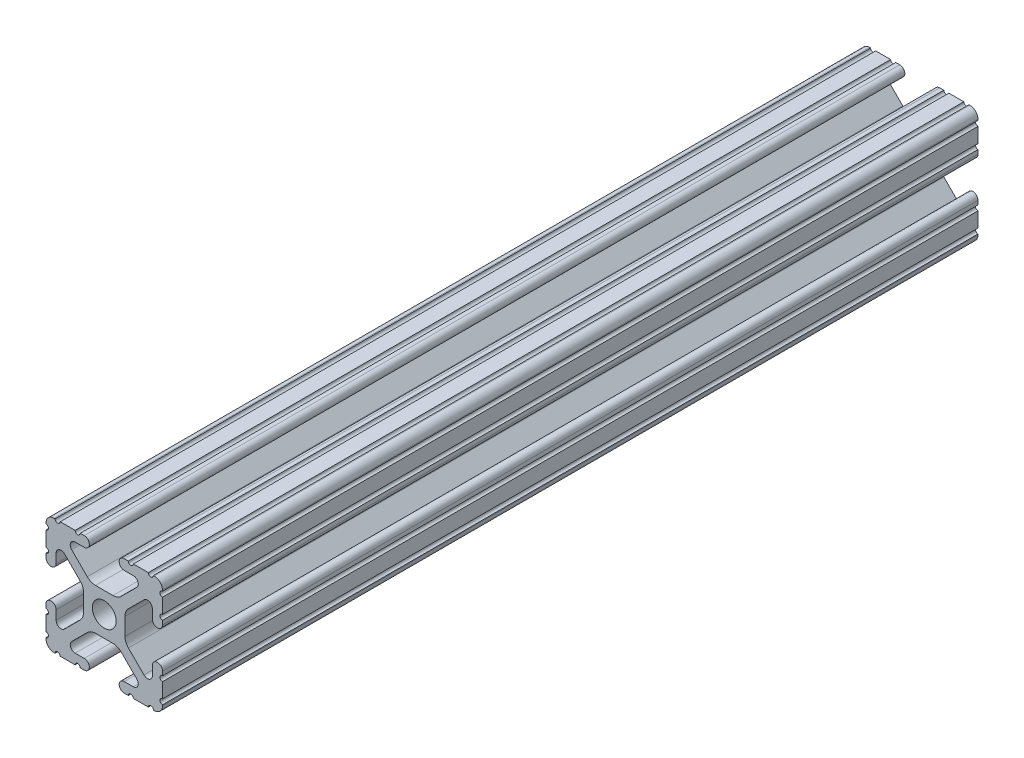
SolidWorks part; units mm, degrees
ref_plane "Front Plane" through (0, 0, 0) normal (0, 0, 1) x (1, 0, 0)
ref_plane "Top Plane" through (0, 0, 0) normal (0, 1, 0) x (1, 0, 0)
ref_plane "Right Plane" through (0, 0, 0) normal (1, 0, 0) x (0, 0, -1)
sketch "Sketch1" plane through (0, 0, 0) normal (0, 0, 1) x (1, 0, 0)
  line L0 (0, -12.7) -> (0, 12.7) construction
  line L1 (12.7, 0) -> (-12.7, 0) construction
  line L2 (3.2512, 12.7) -> (-3.2512, 12.7) construction
  line L3 (0, -4.5212) -> (0, 4.5212) construction
  line L4 (-3.2512, 12.7) -> (-3.2512, 10.4902) construction
  line L5 (12.7, -7.4168) -> (12.7, 7.4168) construction
  line L6 (0, -2.6035) -> (0, 2.6035) construction
  point P4 (0, 0)
  point P8 (0, 0)
  point P11 (0, 12.7)
  point P14 (0, 0)
  point P18 (12.7, 0)
  point P21 (0, 0)
sketch "Sketch2" plane through (0, 0, 0) normal (1, 0, 0) x (0, 0, -1)
  line L0 (-457.2, 0) -> (457.2, 0) construction
  point P4 (0, 0)
  dimension "Length" = 914.4
sketch "Sketch3" plane through (0, 0, 0) normal (0, 0, 1) x (1, 0, 0)
  line L1 (12.7, -12.7) -> (-12.7, -12.7)
  line L2 (12.7, -12.7) -> (12.7, 12.7)
  line L3 (12.7, 12.7) -> (-12.7, 12.7)
  line L4 (-12.7, -12.7) -> (-12.7, 12.7)
  line L5 (12.7, -12.7) -> (-12.7, 12.7) construction
  line L6 (12.7, 12.7) -> (-12.7, -12.7) construction
  point P0 (0, 0)
extrude "Boss-Extrude1" add sketch "Sketch3" along normal blind 177.8
sketch "Sketch4" plane through (0, 0, 177.8) normal (0, 0, 1) x (1, 0, 0)
  line L0 (-3.2512, 12.7) -> (-3.2512, 10.4902)
  line L1 (-3.2512, 10.4902) -> (-8.9276, 10.4902)
  line L2 (-8.9276, 10.4902) -> (-2.9586, 4.5212)
  line L3 (-2.9586, 4.5212) -> (2.9586, 4.5212)
  line L4 (0, -12.7) -> (0, 12.7) construction
  line L5 (12.7, 12.7) -> (-12.7, 12.7) construction
  line L6 (0, 12.7) -> (0, -12.7) construction
  line L7 (-12.7, 0) -> (12.7, 0) construction
  line L8 (-12.7, 12.7) -> (0, 0) construction
  line L9 (-12.7, 3.2512) -> (-10.4902, 3.2512)
  line L10 (-10.4902, 3.2512) -> (-10.4902, 8.9276)
  line L11 (-10.4902, 8.9276) -> (-4.5212, 2.9586)
  line L12 (-4.5212, 2.9586) -> (-4.5212, -2.9586)
  line L13 (4.5212, 2.9586) -> (4.5212, -2.9586)
  line L14 (10.4902, 8.9276) -> (4.5212, 2.9586)
  line L15 (10.4902, 3.2512) -> (10.4902, 8.9276)
  line L16 (12.7, 3.2512) -> (10.4902, 3.2512)
  line L17 (8.9276, 10.4902) -> (2.9586, 4.5212)
  line L18 (3.2512, 10.4902) -> (8.9276, 10.4902)
  line L19 (3.2512, 12.7) -> (3.2512, 10.4902)
  line L20 (3.2512, -12.7) -> (3.2512, -10.4902)
  line L21 (3.2512, -10.4902) -> (8.9276, -10.4902)
  line L22 (8.9276, -10.4902) -> (2.9586, -4.5212)
  line L23 (12.7, -3.2512) -> (10.4902, -3.2512)
  line L24 (10.4902, -3.2512) -> (10.4902, -8.9276)
  line L25 (10.4902, -8.9276) -> (4.5212, -2.9586)
  line L26 (-10.4902, -8.9276) -> (-4.5212, -2.9586)
  line L27 (-10.4902, -3.2512) -> (-10.4902, -8.9276)
  line L28 (-12.7, -3.2512) -> (-10.4902, -3.2512)
  line L29 (-2.9586, -4.5212) -> (2.9586, -4.5212)
  line L30 (-8.9276, -10.4902) -> (-2.9586, -4.5212)
  line L31 (-3.2512, -10.4902) -> (-8.9276, -10.4902)
  line L32 (-3.2512, -12.7) -> (-3.2512, -10.4902)
  line L33 (-12.7, 3.2512) -> (-12.7, -3.2512)
  line L34 (-3.2512, -12.7) -> (3.2512, -12.7)
  line L35 (12.7, -3.2512) -> (12.7, 3.2512)
  line L36 (3.2512, 12.7) -> (-3.2512, 12.7)
  line L37 (-12.7, 12.7) -> (-12.7, -12.7) construction
  line L38 (-12.7, -12.7) -> (12.7, -12.7) construction
  arc A3 (-6.3485, 10.4902) -> (-7.1039, 8.6665) centre (-6.3485, 9.4219) ccw
  arc A4 (7.1039, 8.6665) -> (6.3485, 10.4902) centre (6.3485, 9.4219) ccw
  arc A5 (8.6665, -7.1039) -> (10.4902, -6.3485) centre (9.4219, -6.3485) ccw
  arc A6 (10.4902, 6.3485) -> (8.6665, 7.1039) centre (9.4219, 6.3485) ccw
  arc A7 (-7.1039, -8.6665) -> (-6.3485, -10.4902) centre (-6.3485, -9.4219) ccw
  arc A8 (6.3485, -10.4902) -> (7.1039, -8.6665) centre (6.3485, -9.4219) ccw
  arc A9 (-8.6665, 7.1039) -> (-10.4902, 6.3485) centre (-9.4219, 6.3485) ccw
  arc A10 (-10.4902, -6.3485) -> (-8.6665, -7.1039) centre (-9.4219, -6.3485) ccw
  circle A11 centre (0, 0) radius 2.6035
  point P34 (0, 4.5212)
  point P45 (4.5212, 0)
  point P46 (-4.5212, 0)
  point P53 (0, -4.5212)
  point P81 (0, 0)
  line M2 (-12.7, 12.7) -> (-12.7, -12.7)
  line M3 (-12.7, -12.7) -> (12.7, -12.7)
  line M4 (12.7, -12.7) -> (12.7, 12.7)
  line M5 (12.7, 12.7) -> (-12.7, 12.7)
  dimension "D5" = 5.207
  dimension "D1" = 2.2098
  dimension "D2" = 2.2098
  dimension "D3" = 14.8336
  dimension "D4" = 4
extrude "Cut-Extrude1" cut sketch "Sketch4" against normal through all contours L17 A4 L18 L19 L0 L1 A3 L2 L3 M5 | L15 A6 L14 L13 L25 A5 L24 L23 L16 M4 | L21 A8 L22 L29 L30 A7 L31 L32 L20 M3 | L27 A10 L26 L12 L11 A9 L10 L9 L28 M2 | A11
sketch "Sketch5" plane through (0, 0, 177.8) normal (0, 0, 1) x (1, 0, 0)
  line L0 (-4.3561, 12.7) -> (-3.2512, 12.7)
  line L1 (-3.2512, 12.7) -> (-3.2512, 10.4902)
  line L2 (-3.2512, 10.4902) -> (-4.3561, 10.4902)
  line L3 (0, -12.7) -> (0, 12.7) construction
  line L4 (-3.2512, 12.7) -> (-12.7, 12.7) construction
  line L5 (3.2512, 10.4902) -> (4.3561, 10.4902)
  line L6 (3.2512, 12.7) -> (3.2512, 10.4902)
  line L7 (4.3561, 12.7) -> (3.2512, 12.7)
  line L8 (12.7, 4.3561) -> (12.7, 3.2512)
  line L9 (12.7, 3.2512) -> (10.4902, 3.2512)
  line L10 (10.4902, 3.2512) -> (10.4902, 4.3561)
  line L11 (10.4902, -3.2512) -> (10.4902, -4.3561)
  line L12 (12.7, -3.2512) -> (10.4902, -3.2512)
  line L13 (12.7, -4.3561) -> (12.7, -3.2512)
  line L14 (4.3561, -12.7) -> (3.2512, -12.7)
  line L15 (3.2512, -12.7) -> (3.2512, -10.4902)
  line L16 (3.2512, -10.4902) -> (4.3561, -10.4902)
  line L17 (-3.2512, -10.4902) -> (-4.3561, -10.4902)
  line L18 (-3.2512, -12.7) -> (-3.2512, -10.4902)
  line L19 (-4.3561, -12.7) -> (-3.2512, -12.7)
  line L20 (-12.7, -4.3561) -> (-12.7, -3.2512)
  line L21 (-12.7, -3.2512) -> (-10.4902, -3.2512)
  line L22 (-10.4902, -3.2512) -> (-10.4902, -4.3561)
  line L23 (-10.4902, 3.2512) -> (-10.4902, 4.3561)
  line L24 (-12.7, 3.2512) -> (-10.4902, 3.2512)
  line L25 (-12.7, 4.3561) -> (-12.7, 3.2512)
  line L26 (-12.7, 12.7) -> (-12.7, 3.2512) construction
  line L27 (-10.7124, 12.7) -> (-9.6075, 12.7)
  line L28 (-6.3436, 12.7) -> (-5.2387, 12.7)
  line L29 (-12.7, 10.7124) -> (-12.7, 9.6075)
  line L30 (-12.7, 6.3436) -> (-12.7, 5.2387)
  line L31 (6.3437, 12.7) -> (5.2388, 12.7)
  line L32 (10.7125, 12.7) -> (9.6076, 12.7)
  line L33 (12.7, 10.7125) -> (12.7, 9.6075)
  line L34 (12.7, 6.3436) -> (12.7, 5.2387)
  line L35 (12.7, -6.3437) -> (12.7, -5.2388)
  line L36 (12.7, -10.7125) -> (12.7, -9.6076)
  line L37 (10.7125, -12.7) -> (9.6076, -12.7)
  line L38 (6.3437, -12.7) -> (5.2388, -12.7)
  line L39 (-6.3436, -12.7) -> (-5.2387, -12.7)
  line L40 (-10.7124, -12.7) -> (-9.6075, -12.7)
  line L41 (-12.7, -10.7125) -> (-12.7, -9.6076)
  line L42 (-12.7, -6.3437) -> (-12.7, -5.2388)
  line L43 (12.7, 12.7) -> (3.2512, 12.7) construction
  line L44 (12.7, 3.2512) -> (12.7, 12.7) construction
  arc A0 (-4.3561, 10.4902) -> (-4.3561, 12.7) centre (-4.3561, 11.5951) ccw
  arc A1 (4.3561, 10.4902) -> (4.3561, 12.7) centre (4.3561, 11.5951) cw
  arc A2 (10.4902, 4.3561) -> (12.7, 4.3561) centre (11.5951, 4.3561) ccw
  arc A3 (10.4902, -4.3561) -> (12.7, -4.3561) centre (11.5951, -4.3561) cw
  arc A4 (4.3561, -10.4902) -> (4.3561, -12.7) centre (4.3561, -11.5951) ccw
  arc A5 (-4.3561, -10.4902) -> (-4.3561, -12.7) centre (-4.3561, -11.5951) cw
  arc A6 (-10.4902, -4.3561) -> (-12.7, -4.3561) centre (-11.5951, -4.3561) ccw
  arc A7 (-10.4902, 4.3561) -> (-12.7, 4.3561) centre (-11.5951, 4.3561) cw
  arc A8 (-10.7124, 12.7) -> (-9.6075, 12.7) centre (-10.16, 12.7) ccw
  arc A9 (-6.3436, 12.7) -> (-5.2387, 12.7) centre (-5.7912, 12.7) ccw
  arc A10 (-12.7, 9.6075) -> (-12.7, 10.7124) centre (-12.7, 10.16) ccw
  arc A11 (-12.7, 5.2387) -> (-12.7, 6.3436) centre (-12.7, 5.7912) ccw
  arc A12 (5.2388, 12.7) -> (6.3437, 12.7) centre (5.7912, 12.7) ccw
  arc A13 (9.6076, 12.7) -> (10.7125, 12.7) centre (10.16, 12.7) ccw
  arc A14 (12.7, 10.7125) -> (12.7, 9.6075) centre (12.7, 10.16) ccw
  arc A15 (12.7, 6.3436) -> (12.7, 5.2387) centre (12.7, 5.7912) ccw
  arc A16 (12.7, -5.2388) -> (12.7, -6.3437) centre (12.7, -5.7912) ccw
  arc A17 (12.7, -9.6076) -> (12.7, -10.7125) centre (12.7, -10.16) ccw
  arc A18 (10.7125, -12.7) -> (9.6076, -12.7) centre (10.16, -12.7) ccw
  arc A19 (6.3437, -12.7) -> (5.2388, -12.7) centre (5.7912, -12.7) ccw
  arc A20 (-5.2387, -12.7) -> (-6.3436, -12.7) centre (-5.7912, -12.7) ccw
  arc A21 (-9.6075, -12.7) -> (-10.7124, -12.7) centre (-10.16, -12.7) ccw
  arc A22 (-12.7, -10.7125) -> (-12.7, -9.6076) centre (-12.7, -10.16) ccw
  arc A23 (-12.7, -6.3437) -> (-12.7, -5.2388) centre (-12.7, -5.7912) ccw
  point P11 (0, 0)
  point P52 (0, 0)
  point P104 (0, 0)
  line M5 (3.2512, -10.4902) -> (3.2512, -12.7)
  line M6 (3.2512, -12.7) -> (12.7, -12.7)
  line M7 (12.7, -12.7) -> (12.7, -3.2512)
  line M8 (12.7, -3.2512) -> (10.4902, -3.2512)
  line M9 (10.4902, -3.2512) -> (10.4902, -6.3485)
  line M15 (10.4902, 6.3485) -> (10.4902, 3.2512)
  line M16 (10.4902, 3.2512) -> (12.7, 3.2512)
  line M17 (12.7, 3.2512) -> (12.7, 12.7)
  line M18 (12.7, 12.7) -> (3.2512, 12.7)
  line M19 (3.2512, 12.7) -> (3.2512, 10.4902)
  line M20 (3.2512, 10.4902) -> (6.3485, 10.4902)
  line M26 (-6.3485, 10.4902) -> (-3.2512, 10.4902)
  line M27 (-3.2512, 10.4902) -> (-3.2512, 12.7)
  line M28 (-3.2512, 12.7) -> (-12.7, 12.7)
  line M29 (-12.7, 12.7) -> (-12.7, 3.2512)
  line M30 (-12.7, 3.2512) -> (-10.4902, 3.2512)
  line M31 (-10.4902, 3.2512) -> (-10.4902, 6.3485)
  line M37 (-10.4902, -6.3485) -> (-10.4902, -3.2512)
  line M38 (-10.4902, -3.2512) -> (-12.7, -3.2512)
  line M39 (-12.7, -3.2512) -> (-12.7, -12.7)
  line M40 (-12.7, -12.7) -> (-3.2512, -12.7)
  line M41 (-3.2512, -12.7) -> (-3.2512, -10.4902)
  line M42 (-3.2512, -10.4902) -> (-6.3485, -10.4902)
  line M48 (6.3485, -10.4902) -> (3.2512, -10.4902)
  dimension "D2" = 0.5524
  dimension "D3" = 2.54
  dimension "D4" = 2.54
  dimension "D5" = 2.54
  dimension "D6" = 2.54
  dimension "D1" = 4
  dimension "D7" = 4
extrude "Cut-Extrude2" cut sketch "Sketch5" against normal through all contours A7 M30 M29 | A7 L24 M31 | A6 L21 M39 | A6 M37 M38 | A5 L18 M42 | A5 M41 M40 | A4 M48 M5 | A4 L15 M6 | A3 L12 M9 | A3 M8 M7 | A2 M15 M16 | A2 L9 M17 | A1 M19 M18 | A1 L6 M20 | A0 L1 M28 | A0 M26 M27 | A11 L30 | A10 L29 | A8 L27 | A9 L28 | L31 A12 | L32 A13 | L33 A14 | L34 A15 | L42 A23 | L41 A22 | L40 A21 | L39 A20 | L36 A17 | L35 A16 | L37 A18 | L38 A19
fillet "Fillet1" radius 2.54 8 edges at (2.9586, -4.5212, 88.9) (-2.9586, -4.5212, 88.9) (4.5212, -2.9586, 88.9) (4.5212, 2.9586, 88.9) (-2.9586, 4.5212, 88.9) (2.9586, 4.5212, 88.9) (-4.5212, -2.9586, 88.9) (-4.5212, 2.9586, 88.9)
fillet "Fillet2" radius 1.778 4 edges at (12.7, -12.7, 88.9) (12.7, 12.7, 88.9) (-12.7, -12.7, 88.9) (-12.7, 12.7, 88.9)
equation "\"D2@Sketch4\"=\"Thickness@Sketch1\""
equation "\"D1@Sketch4\"=\"Thickness@Sketch1\""
equation "\"D3@Sketch4\"=\"Opening Width@Sketch1\""
equation "\"D5@Sketch4\"=\"Hole Dia@Sketch1\""
equation "\"D2@Sketch5\"=\"Thickness@Sketch1\"/4"
equation "\"D3@Sketch5\"=\"Height@Sketch1\"/10"
equation "\"D4@Sketch5\"=\"D3@Sketch5\""
equation "\"D5@Sketch5\"=\"D4@Sketch5\""
equation "\"D6@Sketch5\"=\"D5@Sketch5\""
